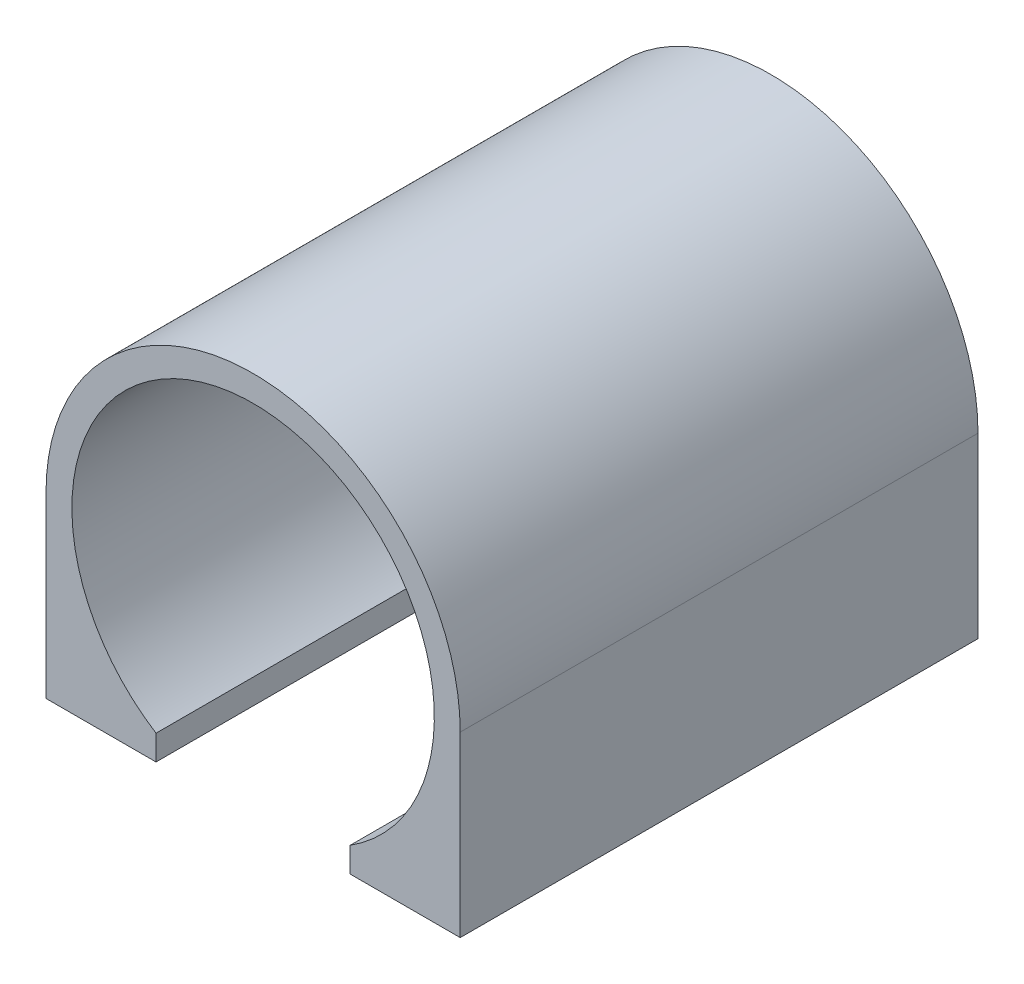
SolidWorks part; units mm, degrees
ref_plane "Front Plane" through (0, 0, 0) normal (0, 0, 1) x (1, 0, 0)
ref_plane "Top Plane" through (0, 0, 0) normal (0, 1, 0) x (1, 0, 0)
ref_plane "Right Plane" through (0, 0, 0) normal (1, 0, 0) x (0, 0, -1)
sketch "Sketch1" plane through (0, 0, 0) normal (0, 0, 1) x (1, 0, 0)
  line L0 (-2.6339, -13.75) -> (-16, -13.75)
  line L4 (0, 0) -> (0, 12.3011) construction
  line L5 (2.6339, -13.75) -> (16, -13.75)
  line L8 (-16, 0) -> (-16, -13.75)
  line L9 (16, 0) -> (16, -13.75)
  arc A1 (2.6339, -13.75) -> (-2.6339, -13.75) centre (0, 0) ccw
  arc A3 (16, 0) -> (-16, 0) centre (0, 0) ccw
  dimension "D1" = 28
  dimension "D2" = 32
  dimension "D4" = 16
  dimension "D3" = 13.75
extrude "Boss-Extrude1" add sketch "Sketch1" along normal blind 40
sketch "Sketch2" plane through (0, -13.75, 0) normal (0, -1, 0) x (1, 0, 0)
  line L0 (0, 0) -> (0, 40) construction
  line L1 (14, 40) -> (-14, 40) construction
  line L2 (13, 40) -> (13, 26.6667) construction
  line L5 (2.6339, 40) -> (16, 40) construction
  line L6 (13, 26.6667) -> (13, 13.3333) construction
  line L7 (13, 13.3333) -> (13, 0) construction
  line L8 (2.6339, 0) -> (16, 0) construction
  line L9 (16, 40) -> (16, 0) construction
  circle A0 centre (13, 33.3333) radius 1.5
  circle A1 centre (13, 20) radius 1.5
  circle A2 centre (13, 6.6667) radius 1.5
  circle A3 centre (-13, 6.6667) radius 1.5
  circle A4 centre (-13, 20) radius 1.5
  circle A5 centre (-13, 33.3333) radius 1.5
  dimension "D1" = 3
  dimension "D2" = 3
extrude "Cut-Extrude1" cut sketch "Sketch2" against normal blind 3
sketch "Sketch3" plane through (0, 0, 40) normal (0, 0, 1) x (1, 0, 0)
  line L0 (-16, -13.75) -> (16, -13.75) construction
  line L1 (-7.5, -13.75) -> (7.5, -13.75)
  point P7 (0, -13.75)
  dimension "D1" = 15
extrude "Cut-Extrude-Thin1" cut sketch "Sketch3" against normal through all thin thin type one direction reverse wall 10
